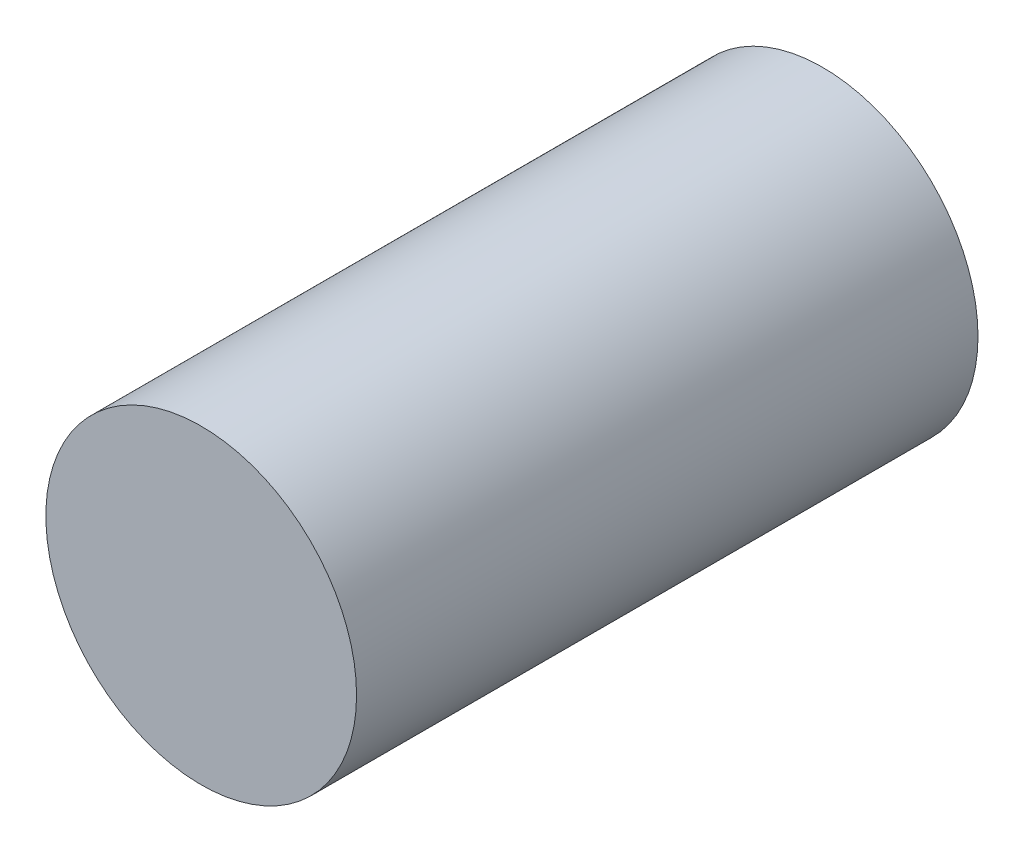
SolidWorks part; units mm, degrees
ref_plane "前视基准面" through (0, 0, 0) normal (0, 0, 1) x (1, 0, 0)
ref_plane "上视基准面" through (0, 0, 0) normal (0, 1, 0) x (1, 0, 0)
ref_plane "右视基准面" through (0, 0, 0) normal (1, 0, 0) x (0, 0, -1)
other "Configuration Table"
sketch "草图1" plane through (0, 0, 0) normal (0, 0, 1) x (1, 0, 0)
  circle A0 centre (0, 0) radius 25
  dimension "D1" = 50
extrude "凸台-拉伸1" add sketch "草图1" along normal blind 100
